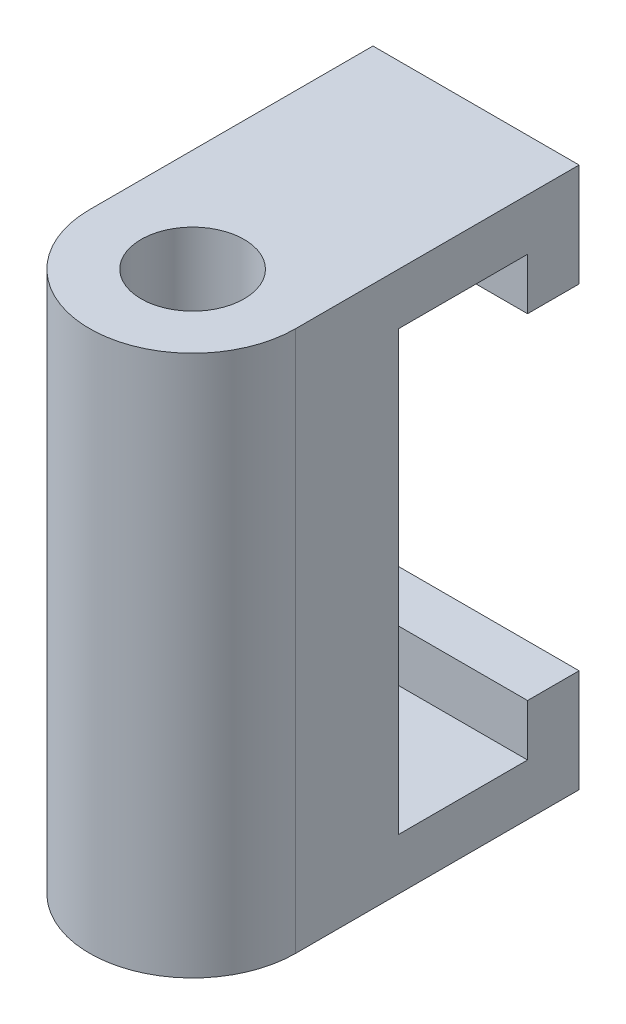
SolidWorks part; units mm, degrees
ref_plane "Front Plane" through (0, 0, 0) normal (0, 0, 1) x (1, 0, 0)
ref_plane "Top Plane" through (0, 0, 0) normal (0, 1, 0) x (1, 0, 0)
ref_plane "Right Plane" through (0, 0, 0) normal (1, 0, 0) x (0, 0, -1)
sketch "Sketch1" plane through (0, 0, 0) normal (0, 1, 0) x (1, 0, 0)
  line L0 (-3.175, 0) -> (-3.175, 8.7312)
  line L1 (-3.175, 8.7312) -> (3.175, 8.7312)
  line L2 (3.175, 8.7312) -> (3.175, 0)
  circle A0 centre (0, 0) radius 1.5875
  circle A1 centre (0, 0) radius 3.175 construction
  arc A2 (-3.175, 0) -> (3.175, 0) centre (0, 0) ccw
  dimension "D1" = 3.175
  dimension "D2" = 1.5875
  dimension "D3" = 8.7312
extrude "Boss-Extrude1" add sketch "Sketch1" along normal blind 16.6687
sketch "Sketch3" plane through (3.175, 0, 0) normal (1, 0, 0) x (0, 0, -1)
  line L0 (8.7312, 13.4937) -> (7.1437, 13.4937)
  line L1 (8.7312, 16.6687) -> (8.7312, 0) construction
  line L2 (7.1437, 13.4937) -> (7.1438, 15.0813)
  line L3 (7.1438, 15.0813) -> (3.175, 15.0813)
  line L4 (3.175, 15.0813) -> (3.175, 1.5875)
  line L5 (3.175, 1.5875) -> (7.1438, 1.5875)
  line L6 (7.1438, 1.5875) -> (7.1438, 3.175)
  line L7 (7.1438, 3.175) -> (8.7312, 3.175)
  line L8 (8.7312, 3.175) -> (8.7312, 13.4937)
  line L9 (0, 16.6687) -> (8.7312, 16.6687) construction
  dimension "D1" = 1.5875
  dimension "D2" = 3.9688
  dimension "D3" = 13.4937
  dimension "D4" = 1.5875
  dimension "D5" = 1.5875
extrude "Cut-Extrude1" cut sketch "Sketch3" against normal through all
